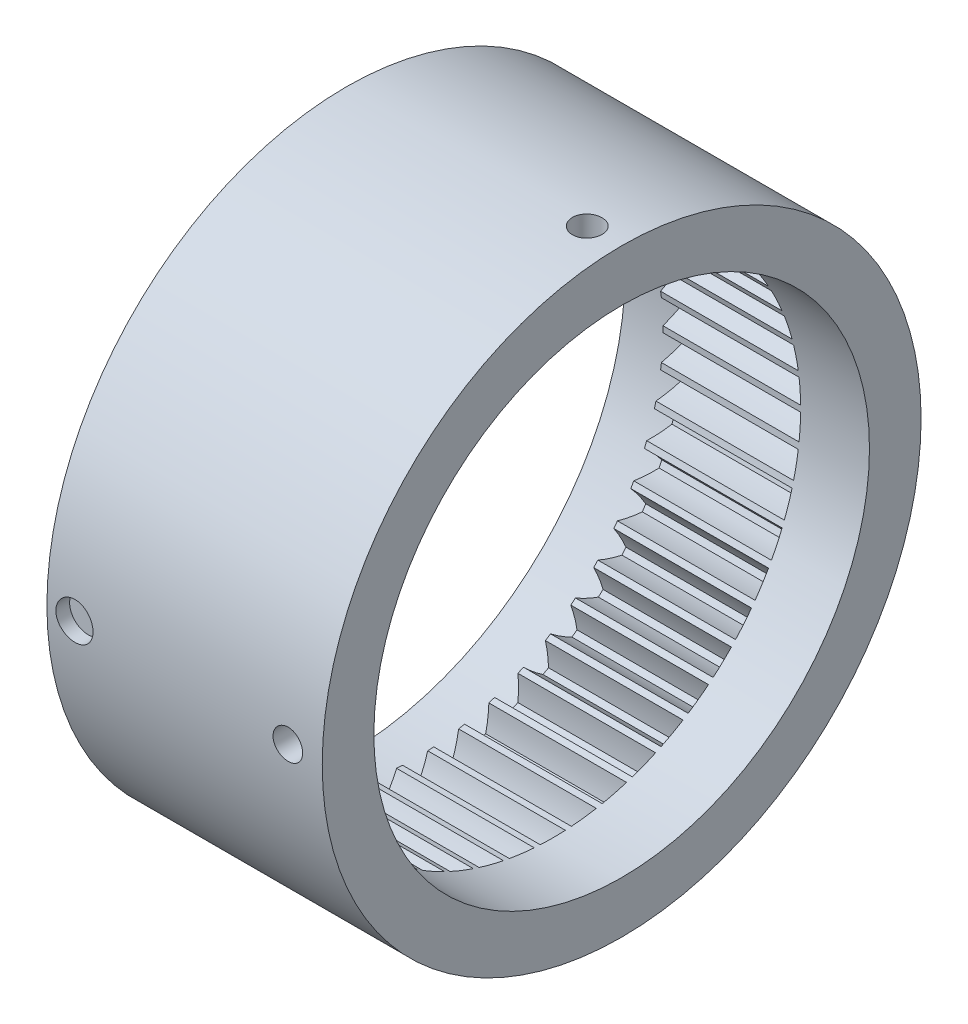
SolidWorks part; units mm, degrees
ref_plane "Plane1" through (0, 0, 0) normal (0, 0, 1) x (1, 0, 0)
ref_plane "Plane2" through (0, 0, 0) normal (0, 1, 0) x (1, 0, 0)
ref_plane "Plane3" through (0, 0, 0) normal (1, 0, 0) x (0, 0, -1)
other "Configuration Table"
sketch "HoldingSke" plane through (0, 0, 0) normal (0, 1, 0) x (1, 0, 0)
  line L0 (0, 0) -> (0.4285, -0.5107)
  line L1 (-15, 0) -> (100, 0) construction
  line L2 (0, 0) -> (-2.1039, 2.3779)
  line L3 (0, 0) -> (-11.863, 4.5341)
  line L4 (0, 0) -> (5.5511, 6.6156)
  line L5 (0, 0) -> (-23.7986, -8.8762)
  line L6 (0, 0) -> (-10.5278, -7.1032)
  line L7 (-2.1039, 2.3779) -> (3.3635, 27.1825)
  line L8 (-76.2, 3.8779) -> (-54.61, 3.8779)
  line L9 (-71.009, 38.7566) -> (-53.1078, 45.2721)
  line L10 (-76.2, 71.12) -> (104.1128, 71.12)
  line L11 (0, 0) -> (-20, 0)
  line L12 (-76.2, 101.6) -> (-76.147, 101.6)
  line L13 (24.9733, 27.94) -> (52.9518, 28.4284)
  line L14 (24.9733, 27.94) -> (24.9743, 27.94)
  line L15 (24.9733, 27.94) -> (100.4006, 29.5858)
  circle A0 centre (0, 0) radius 43.5
  circle A1 centre (0, 0) radius 12.7
  circle A2 centre (0, 0) radius 12.7
  dimension "MHD" = 25.4
  dimension "Hub_dia" = 25.4
  dimension "Diameter" = 87
  dimension "Num_teeth" = 50
  dimension "Pitch" = 0.6667
  dimension "Overall_len" = 25.4
  dimension "Show_teeth" = 50
  dimension "Thickness" = 12.7
  dimension "OAL" = 25.4001
  dimension "T_dim" = 21.59
  dimension "Ap" = 20
  dimension "H" = 19.05
  dimension "Pitch_radius" = 180.3128
  dimension "Width" = 20
  dimension "Backlash" = 0.053
  dimension "Addendum_fac" = 1
  dimension "Dedendum_fac" = 1.25
  dimension "Clearance_fac" = 0.25
  dimension "Dedendum_add" = 0.001
  dimension "Module" = 1.5
sketch "BasProSke" plane through (0, 0, 0) normal (0, 1, 0) x (1, 0, 0)
  line L0 (-10, 0) -> (60, 0) construction
  line L1 (0, 36) -> (0, 43.5)
  line L2 (0, 36) -> (20, 36)
  line L3 (20, 36) -> (20, 43.5)
  line L4 (20, 43.5) -> (0, 43.5)
  dimension "Diameter" = 87
  dimension "Thickness" = 20
  dimension "Inside_diameter" = 72
revolve "Base-Revolve" add sketch "BasProSke" angle 360 about L0
sketch "TooCutSke" plane through (0, 0, 0) normal (1, 0, 0) x (0, 0, -1)
  line L3 (1.3104, 37.4771) -> (1.3104, 53.6633) construction
  line L4 (0, 0) -> (0, 59.563) construction
  line L5 (0, 0) -> (-4.2903, 68.1927) construction
  line L6 (-16.1945, 30.7585) -> (35.7768, 34.0282) construction
  circle A0 centre (0, 0) radius 37.5 construction
  circle A1 centre (0, 0) radius 39.376 construction
  circle A2 centre (0, 0) radius 31.7146 construction
  circle A3 centre (0, 0) radius 35.9746 construction
  arc A4 (1.8287, 35.9281) -> (0.4592, 39.3733) centre (-16.1945, 30.7585) ccw
  arc A5 (1.8287, 35.9281) -> (-1.8287, 35.9281) centre (0, 0) ccw
  arc A6 (0.4592, 39.3733) -> (-0.4592, 39.3733) centre (0, 0) ccw
  arc A7 (-0.4592, 39.3733) -> (-1.8287, 35.9281) centre (16.1945, 30.7585) ccw
  dimension "Pitch_dia" = 75
  dimension "Base_dia" = 63.4293
  dimension "Root_dia" = 78.752
  dimension "Overcut_dia" = 71.9492
  dimension "Flank_rad" = 18.75
  dimension "Half_ang" = 3.6
  dimension "Half_CT" = 1.3104
extrude "ToothCut" cut sketch "TooCutSke" along normal through all
fillet "Breaks" [suppressed] radius 0.15
fillet "RootFillets" [suppressed] radius 0.376
pattern_circular "TeethCuts" count 50 every 7.2 about axis through (-10, 0, 0) along (1, 0, 0) of "RootFillets", "Breaks", "ToothCut"
sketch "Sketch1" plane through (20, 0, 0) normal (1, 0, 0) x (0, 0, -1)
  circle A0 centre (0, 0) radius 43.5
  circle A1 centre (0, 0) radius 36
extrude "Boss-Extrude1" add sketch "Sketch1" along normal blind 10
ref_plane "Plane4" through (0, 0, 43.5) normal (0, 0, 1) x (1, 0, 0)
sketch "Sketch2" plane through (0, 0, 43.5) normal (0, 0, 1) x (1, 0, 0)
  line L0 (30, -43.5) -> (30, 43.5) construction
  line L1 (25, 0) -> (30, 0) construction
  circle A0 centre (25, 0) radius 2.15
  dimension "D2" = 4.3
  dimension "D1" = 5
extrude "Cut-Extrude1" cut sketch "Sketch2" against normal blind 7
pattern_circular "CirPattern1" count 4 over 360 about axis through (0, 0, 0) along (1, 0, 0) of "Cut-Extrude1"
sketch "Sketch3" plane through (0, 0, 0) normal (-1, 0, 0) x (0, 0, 1)
  circle A0 centre (0, 0) radius 43.5 construction
  circle A1 centre (0, 0) radius 43.5
  circle A2 centre (0, 0) radius 40.5
  dimension "D1" = 3
extrude "Boss-Extrude2" add sketch "Sketch3" along normal blind 10
sketch "Sketch4" plane through (0, 0, 43.5) normal (0, 0, 1) x (1, 0, 0)
  line L0 (-10, 43.5) -> (-10, -43.5) construction
  circle A0 centre (-6, 0) radius 2.7
  dimension "D1" = 5.4
  dimension "D2" = 4
extrude "Cut-Extrude2" cut sketch "Sketch4" against normal blind 2
equation "' \"Module@HoldingSke\" = 6.35"
equation "' \"Num_teeth@HoldingSke\" = 24"
equation "' \"Ap@HoldingSke\" =  14.5"
equation "' \"Ap@HoldingSke\" = 14.5"
equation "' \"Width@HoldingSke\" = 12"
equation "' \"Diameter@HoldingSke\" = 8 * 25.4"
equation "' \"Show_teeth@HoldingSke\" = 100"
equation "' \"Backlash@HoldingSke\" = 0.009 * 25.4"
equation "' \"Addendum_fac@HoldingSke\" = 1.0"
equation "' \"Dedendum_fac@HoldingSke\" = 1.25"
equation "' \"Dedendum_add@HoldingSke\" = 0.00005 * 25.4"
equation "' \"Clearance_fac@HoldingSke\" = 0.25"
equation "\"Pitch@HoldingSke\" = 1 / \"Module@HoldingSke\" "
equation "\"Overcut_dia@TooCutSke\" = (\"Num_teeth@HoldingSke\" - 2 * \"Addendum_fac@HoldingSke\") / \"Pitch@HoldingSke\" - 0.002 * 25.4"
equation "\"Pitch_dia@TooCutSke\" = \"Num_teeth@HoldingSke\" / \"Pitch@HoldingSke\""
equation "\"Base_dia@TooCutSke\" = \"Num_teeth@HoldingSke\" / \"Pitch@HoldingSke\" * cos((\"Ap@HoldingSke\"  * 3.14159265 / 180)) * 0.90"
equation "\"Root_dia@TooCutSke\" = \"Num_teeth@HoldingSke\"  / \"Pitch@HoldingSke\" + 2 *  \"Dedendum_fac@HoldingSke\"/ \"Pitch@HoldingSke\" + \"Dedendum_add@HoldingSke\" * 2"
equation "\"Half_ang@TooCutSke\" = 180 / \"Num_teeth@HoldingSke\""
equation "\"Half_CT@TooCutSke\" = \"Num_teeth@HoldingSke\" / \"Pitch@HoldingSke\" * sin((3.14159265 / 2 / \"Num_teeth@HoldingSke\")) / 2 + 10 * \"Backlash@HoldingSke\" / 4"
equation "\"Flank_rad@TooCutSke\" = \"Num_teeth@HoldingSke\" / \"Pitch@HoldingSke\" / 4"
equation "\"Radius@RootFillets\"= \"Clearance_fac@HoldingSke\" / \"Pitch@HoldingSke\" + \"Dedendum_add@HoldingSke\""
equation "\"Break_rad@Breaks\" = 0.02 / \"Pitch@HoldingSke\" * 5"
equation "\"Num_teeth@TeethCuts\" = int( \"Show_teeth@HoldingSke\" ) + 1"
equation "\"Num_teeth@TeethCuts\" = ((sgn( \"Num_teeth@TeethCuts\" - \"Num_teeth@HoldingSke\" )-1)*( \"Num_teeth@TeethCuts\" - \"Num_teeth@HoldingSke\" ))/-2+ \"Num_teeth@HoldingSke\""
equation "\"Num_teeth@TeethCuts\" = ((sgn( \"Num_teeth@TeethCuts\" - 2.0)+1)*( \"Num_teeth@TeethCuts\" - 2.0))/2 +2.0"
equation "\"Angle@TeethCuts\" = 360.0 / \"Num_teeth@HoldingSke\""
equation "\"Diameter@BasProSke\" = \"Num_teeth@HoldingSke\"  / \"Pitch@HoldingSke\" + 2 *  \"Dedendum_fac@HoldingSke\"/ \"Pitch@HoldingSke\" + \"Dedendum_add@HoldingSke\" * 2 + 0.002 * 25.4"
equation "\"Diameter@BasProSke\" = ((sgn( \"Diameter@BasProSke\"  - \"Diameter@HoldingSke\" )+1)*( \"Diameter@BasProSke\"  - \"Diameter@HoldingSke\" ))/2 + \"Diameter@HoldingSke\""
equation "\"Inside_diameter@BasProSke\" =  (\"Num_teeth@HoldingSke\" - 2 * \"Addendum_fac@HoldingSke\") / \"Pitch@HoldingSke\" "
equation "\"Thickness@BasProSke\"  = \"Width@HoldingSke\""
